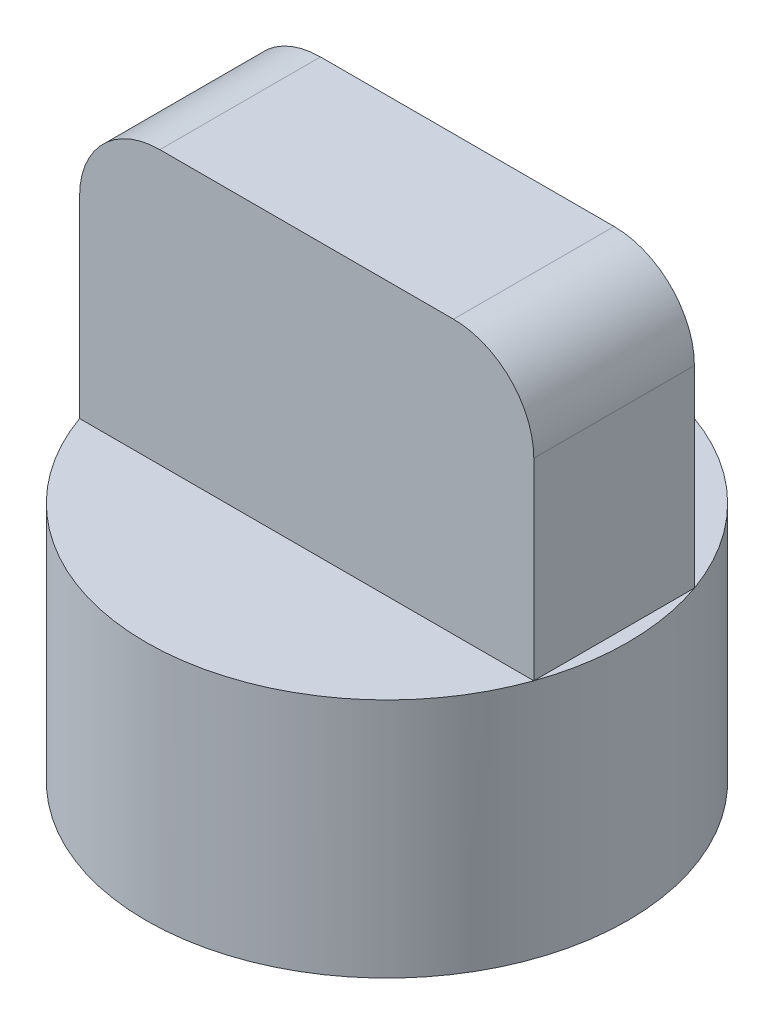
SolidWorks part; units mm, degrees
ref_plane "Front Plane" through (0, 0, 0) normal (0, 0, 1) x (1, 0, 0)
ref_plane "Top Plane" through (0, 0, 0) normal (0, 1, 0) x (1, 0, 0)
ref_plane "Right Plane" through (0, 0, 0) normal (1, 0, 0) x (0, 0, -1)
sketch "Sketch1" plane through (0, 0, 0) normal (0, 1, 0) x (1, 0, 0)
  line L1 (-14.1421, 5) -> (14.1421, 5)
  line L2 (-14.1421, 5) -> (-14.1421, -5)
  line L3 (-14.1421, -5) -> (14.1421, -5)
  line L4 (14.1421, 5) -> (14.1421, -5)
  line L5 (-14.1421, 5) -> (14.1421, -5) construction
  line L6 (-14.1421, -5) -> (14.1421, 5) construction
  circle A0 centre (0, 0) radius 15
  point P7 (0, 0)
  point P8 (-13.4655, -13.6466)
  dimension "D1" = 30
  dimension "D2" = 10
extrude "Boss-Extrude1" add sketch "Sketch1" against normal blind 15 contours L3 A0 | L4 L1 L2 L3 | L4 A0 | L1 A0
sketch "Sketch4" plane through (0, 0, 0) normal (0, 1, 0) x (1, 0, 0)
  line L1 (-14.1421, 5) -> (14.1421, 5)
  line L2 (-14.1421, 5) -> (-14.1421, -5)
  line L3 (-14.1421, -5) -> (14.1421, -5)
  line L4 (14.1421, 5) -> (14.1421, -5)
extrude "Boss-Extrude3" add sketch "Sketch4" along normal blind 17
fillet "Fillet3" radius 5 2 edges at (14.1421, 17, 0) (-14.1421, 17, 0)
